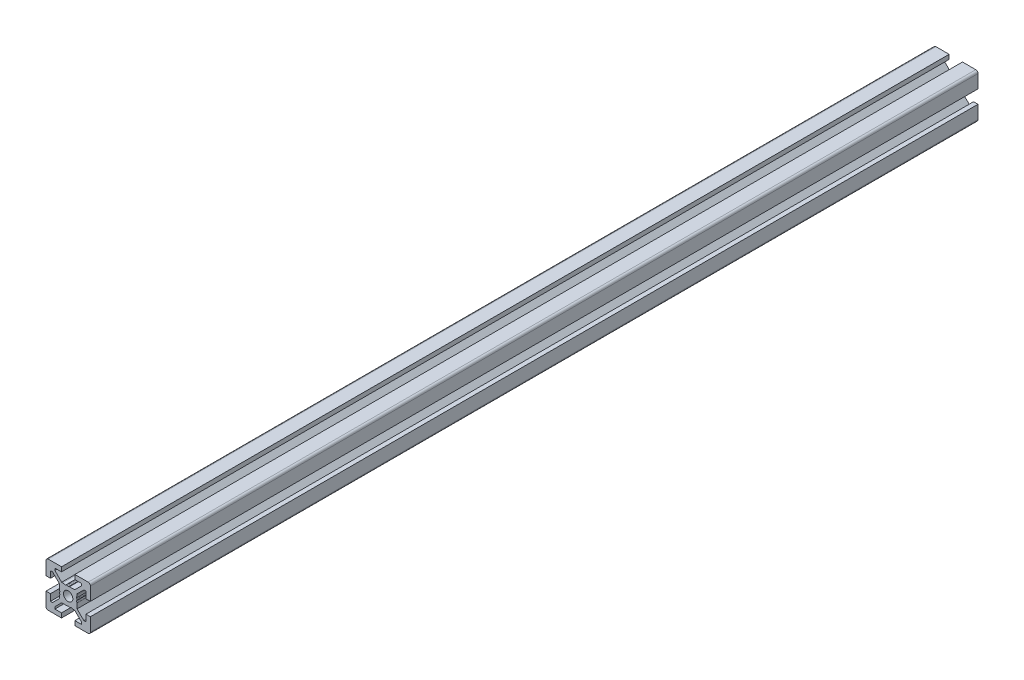
SolidWorks part; units mm, degrees
ref_plane "Front Plane" through (0, 0, 0) normal (0, 0, 1) x (1, 0, 0)
ref_plane "Top Plane" through (0, 0, 0) normal (0, 1, 0) x (1, 0, 0)
ref_plane "Right Plane" through (0, 0, 0) normal (1, 0, 0) x (0, 0, -1)
ref_plane "Plane1" through (0, 0, -2000) normal (0, 0, -1) x (-1, 0, 0)
sketch "Sketch1" plane through (0, 0, -2000) normal (0, 0, -1) x (-1, 0, 0)
  line L0 (10, -3) -> (8, -3)
  line L1 (8, -3) -> (8, -6)
  line L2 (8, -6) -> (7.0607, -6)
  line L3 (7.0607, -6) -> (4, -2.9393)
  line L4 (4, -2.9393) -> (4, -2.5)
  line L5 (4, -2.5) -> (3.751, -1.2189)
  line L6 (3.751, -1.2189) -> (3.933, -0.9036)
  line L7 (3.933, -0.4036) -> (3.7, 0)
  line L8 (3.7, 0) -> (3.933, 0.4036)
  line L9 (4, 0.6536) -> (4, 2.9393)
  line L10 (4, 2.9393) -> (7.0607, 6)
  line L11 (7.0607, 6) -> (8, 6)
  line L12 (8, 6) -> (8, 3)
  line L13 (8, 3) -> (10, 3)
  line L14 (10, 3) -> (10, 9)
  line L15 (9, 10) -> (3, 10)
  line L16 (3, 10) -> (3, 8)
  line L17 (3, 8) -> (6, 8)
  line L18 (6, 8) -> (6, 7.0607)
  line L19 (6, 7.0607) -> (2.9393, 4)
  line L20 (2.9393, 4) -> (2.5, 4)
  line L21 (2.5, 4) -> (1.2189, 3.751)
  line L22 (1.2189, 3.751) -> (0.9036, 3.933)
  line L23 (0.4036, 3.933) -> (0, 3.7)
  line L24 (0, 3.7) -> (-0.4036, 3.933)
  line L25 (-0.6536, 4) -> (-2.9393, 4)
  line L26 (-2.9393, 4) -> (-6, 7.0607)
  line L27 (-6, 7.0607) -> (-6, 8)
  line L28 (-6, 8) -> (-3, 8)
  line L29 (-3, 8) -> (-3, 10)
  line L30 (-3, 10) -> (-9, 10)
  line L31 (-10, 9) -> (-10, 3)
  line L32 (-10, 3) -> (-8, 3)
  line L33 (-8, 3) -> (-8, 6)
  line L34 (-8, 6) -> (-7.0607, 6)
  line L35 (-7.0607, 6) -> (-4, 2.9393)
  line L36 (-4, 2.9393) -> (-4, 2.5)
  line L37 (-4, 2.5) -> (-3.751, 1.2189)
  line L38 (-3.751, 1.2189) -> (-3.933, 0.9036)
  line L39 (-3.933, 0.4036) -> (-3.7, 0)
  line L40 (-3.7, 0) -> (-3.933, -0.4036)
  line L41 (-4, -0.6536) -> (-4, -2.9393)
  line L42 (-4, -2.9393) -> (-7.0607, -6)
  line L43 (-7.0607, -6) -> (-8, -6)
  line L44 (-8, -6) -> (-8, -3)
  line L45 (-8, -3) -> (-10, -3)
  line L46 (-10, -3) -> (-10, -9)
  line L47 (-9, -10) -> (-3, -10)
  line L48 (-3, -10) -> (-3, -8)
  line L49 (-3, -8) -> (-6, -8)
  line L50 (-6, -8) -> (-6, -7.0607)
  line L51 (-6, -7.0607) -> (-2.9393, -4)
  line L52 (-2.9393, -4) -> (-2.5, -4)
  line L53 (-2.5, -4) -> (-1.2189, -3.751)
  line L54 (-1.2189, -3.751) -> (-0.9036, -3.933)
  line L55 (-0.4036, -3.933) -> (0, -3.7)
  line L56 (0, -3.7) -> (0.4036, -3.933)
  line L57 (0.6536, -4) -> (2.9393, -4)
  line L58 (2.9393, -4) -> (6, -7.0607)
  line L59 (6, -7.0607) -> (6, -8)
  line L60 (6, -8) -> (3, -8)
  line L61 (3, -8) -> (3, -10)
  line L62 (3, -10) -> (9, -10)
  line L63 (10, -9) -> (10, -3)
  circle A0 centre (0, 0) radius 2.1
  arc A1 (3.933, -0.9036) -> (3.933, -0.4036) centre (3.5, -0.6536) ccw
  arc A2 (3.933, 0.4036) -> (4, 0.6536) centre (3.5, 0.6536) ccw
  arc A3 (10, 9) -> (9, 10) centre (9, 9) ccw
  arc A4 (0.9036, 3.933) -> (0.4036, 3.933) centre (0.6536, 3.5) ccw
  arc A5 (-0.4036, 3.933) -> (-0.6536, 4) centre (-0.6536, 3.5) ccw
  arc A6 (-9, 10) -> (-10, 9) centre (-9, 9) ccw
  arc A7 (-3.933, 0.9036) -> (-3.933, 0.4036) centre (-3.5, 0.6536) ccw
  arc A8 (-3.933, -0.4036) -> (-4, -0.6536) centre (-3.5, -0.6536) ccw
  arc A9 (-10, -9) -> (-9, -10) centre (-9, -9) ccw
  arc A10 (-0.9036, -3.933) -> (-0.4036, -3.933) centre (-0.6536, -3.5) ccw
  arc A11 (0.4036, -3.933) -> (0.6536, -4) centre (0.6536, -3.5) ccw
  arc A12 (9, -10) -> (10, -9) centre (9, -9) ccw
extrude "Boss-Extrude1" add sketch "Sketch1" against normal blind 400
